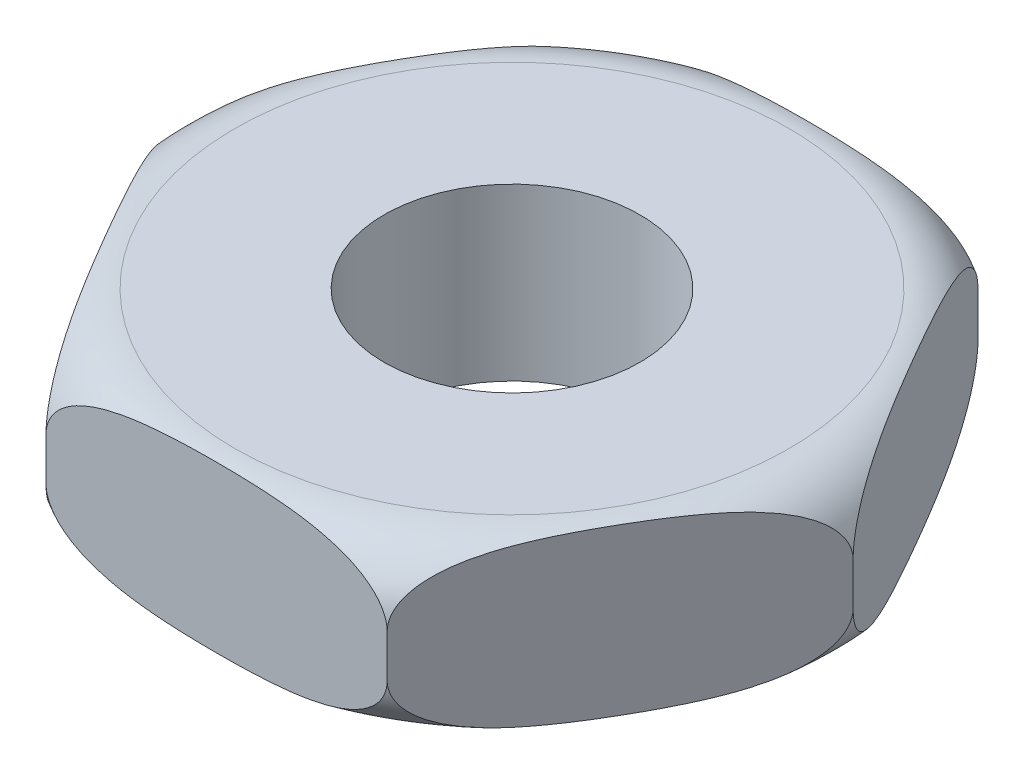
SolidWorks part; units mm, degrees
ref_plane "Front Plane" through (0, 0, 0) normal (0, 0, 1) x (1, 0, 0)
ref_plane "Top Plane" through (0, 0, 0) normal (0, 1, 0) x (1, 0, 0)
ref_plane "Right Plane" through (0, 0, 0) normal (1, 0, 0) x (0, 0, -1)
sketch "Sketch1" plane through (0, 0, 0) normal (0, 1, 0) x (1, 0, 0)
  line L1 (16, 0) -> (8, 13.8564)
  line L2 (8, 13.8564) -> (-8, 13.8564)
  line L3 (-8, 13.8564) -> (-16, 0)
  line L4 (-16, 0) -> (-8, -13.8564)
  line L5 (-8, -13.8564) -> (8, -13.8564)
  line L6 (8, -13.8564) -> (16, 0)
  circle A0 centre (0, 0) radius 13.8564 construction
  circle A1 centre (0, 0) radius 6
  dimension "D2" = 12
  dimension "D1" = 32
extrude "Boss-Extrude1" add sketch "Sketch1" along normal mid plane 8
sketch "Sketch2" plane through (0, 0, 0) normal (0, 0, 1) x (1, 0, 0)
  line L1 (0, 9.3696) -> (0, -11.0399) construction
  line L6 (13, 4) -> (16, 4)
  line L7 (16, 4) -> (16, 1)
  line L8 (13, -4) -> (16, -4)
  line L9 (16, -4) -> (16, -1)
  arc A0 (16, -1) -> (13, -4) centre (13, -1) cw
  arc A1 (16, 1) -> (13, 4) centre (13, 1) ccw
  dimension "D1" = 3
revolve "Cut-Revolve1" cut sketch "Sketch2" angle 360 about L1
